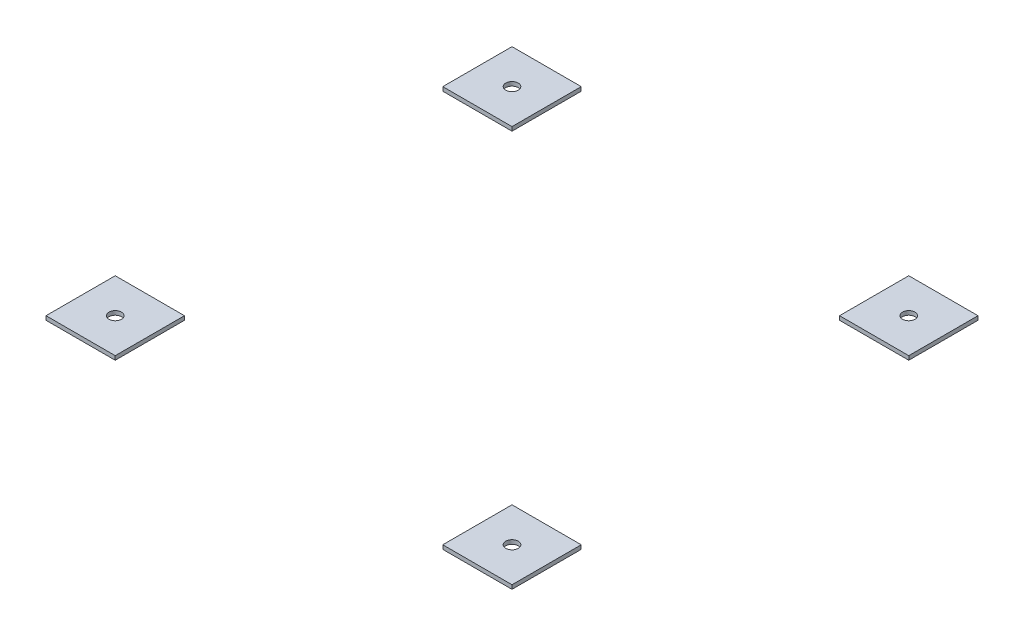
SolidWorks part; units mm, degrees
ref_plane "Front Plane" through (0, 0, 0) normal (0, 0, 1) x (1, 0, 0)
ref_plane "Top Plane" through (0, 0, 0) normal (0, 1, 0) x (1, 0, 0)
ref_plane "Right Plane" through (0, 0, 0) normal (1, 0, 0) x (0, 0, -1)
sketch "Sketch1" plane through (0, 0, 0) normal (0, 1, 0) x (1, 0, 0)
  line L1 (123, 123) -> (175, 123)
  line L2 (123, 123) -> (123, 175)
  line L3 (123, 175) -> (175, 175)
  line L4 (175, 123) -> (175, 175)
  line L5 (-175, 123) -> (-123, 123)
  line L6 (-175, 123) -> (-175, 175)
  line L7 (-175, 175) -> (-123, 175)
  line L8 (-123, 123) -> (-123, 175)
  line L9 (123, -175) -> (175, -175)
  line L10 (123, -175) -> (123, -123)
  line L11 (123, -123) -> (175, -123)
  line L12 (175, -175) -> (175, -123)
  line L13 (-175, -175) -> (-123, -175)
  line L14 (-175, -175) -> (-175, -123)
  line L15 (-175, -123) -> (-123, -123)
  line L16 (-123, -175) -> (-123, -123)
  circle A0 centre (149, 149) radius 4.68
  circle A1 centre (-149, 149) radius 4.68
  circle A2 centre (149, -149) radius 4.68
  circle A3 centre (-149, -149) radius 4.68
extrude "Base plate corner tabs" add sketch "Sketch1" along normal mid plane 3
